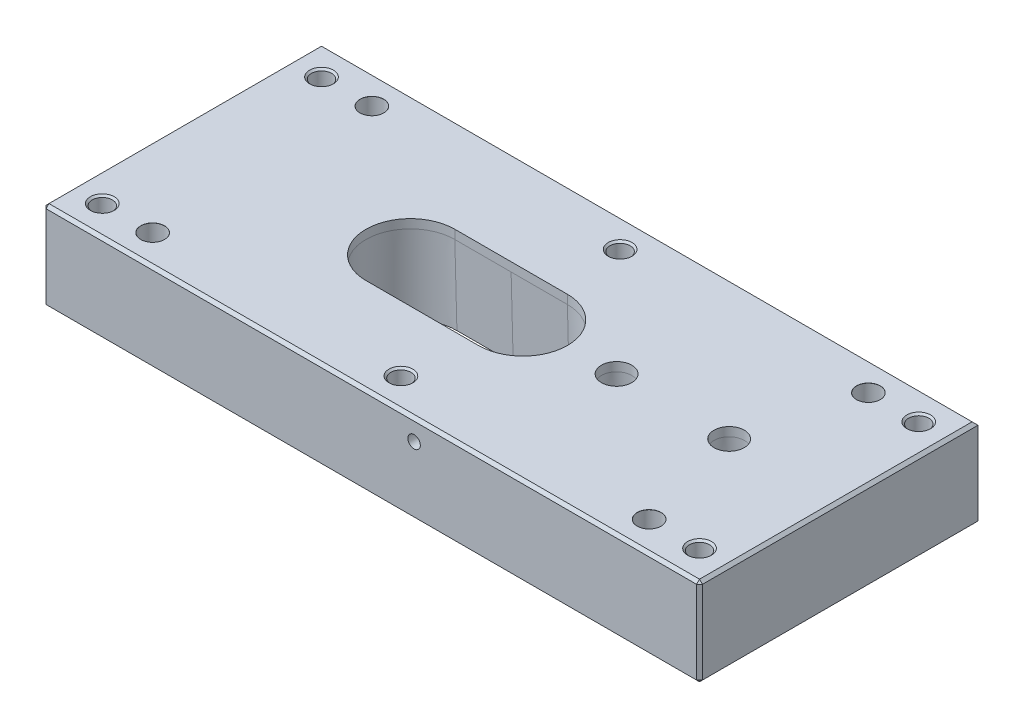
SolidWorks part; units mm, degrees
material "1.2316 (X36CrMo17)"
ref_plane "Front Plane" through (0, 0, 0) normal (0, 0, 1) x (1, 0, 0)
ref_plane "Top Plane" through (0, 0, 0) normal (0, 1, 0) x (1, 0, 0)
ref_plane "Right Plane" through (0, 0, 0) normal (1, 0, 0) x (0, 0, -1)
sketch "Sketch1" plane through (0, 0, 0) normal (0, 1, 0) x (1, 0, 0)
  line L1 (-110.8, 47) -> (110.8, 47)
  line L2 (-110.8, 47) -> (-110.8, -47)
  line L3 (-110.8, -47) -> (110.8, -47)
  line L4 (110.8, 47) -> (110.8, -47)
  line L5 (-110.8, 47) -> (110.8, -47) construction
  line L6 (-110.8, -47) -> (110.8, 47) construction
  point P0 (0, 0)
  dimension "D1" = 94
  dimension "D2" = 221.6
extrude "Boss-Extrude1" add sketch "Sketch1" against normal blind 30
sketch "Sketch2" plane through (0, 0, 0) normal (0, 1, 0) x (1, 0, 0)
  line L0 (-110.8, 0) -> (110.8, 0) construction
  line L1 (-110.8, 47) -> (-110.8, -47) construction
  line L2 (110.8, -47) -> (110.8, 47) construction
  line L3 (0, 47) -> (0, -47) construction
  line L4 (110.8, 47) -> (-110.8, 47) construction
  line L5 (-110.8, -47) -> (110.8, -47) construction
  line L6 (-33.8, 15) -> (4.2, 15)
  line L11 (-33.8, -15) -> (4.2, -15)
  line L12 (-48.8, 16.2329) -> (-48.8, -16.2329) construction
  arc A3 (-33.8, 15) -> (-33.8, -15) centre (-33.8, 0) ccw
  arc A4 (4.2, -15) -> (4.2, 15) centre (4.2, 0) ccw
  circle A5 centre (35.8, 0) radius 5.12
  circle A6 centre (73.8, 0) radius 5.12
  dimension "D1" = 15
  dimension "D3" = 10.24
  dimension "D2" = 38
  dimension "D4" = 38
  dimension "D5" = 62
  dimension "D6" = 69.6
extrude "Cut-Extrude1" cut sketch "Sketch2" against normal through all
ref_plane "Plane1" through (-14.8, 0, 0) normal (1, 0, 0) x (0, 0, -1)
sketch "Sketch3" plane through (-14.8, 0, 0) normal (1, 0, 0) x (0, 0, -1)
  line L0 (15, -3) -> (15.707, -30)
  line L1 (15, -30) -> (15, 0) construction
  line L2 (-47, -30) -> (47, -30) construction
  line L3 (15.707, -30) -> (15, -30)
  line L4 (15, -30) -> (15, -3)
  line L5 (51.7, 0) -> (-51.7, 0) construction
  dimension "D1" = 3
  dimension "D2" = 1.5
curve "CompCurve1"
sweep "Cut-Sweep1" cut profiles "Sketch3" path "CompCurve1"
ref_plane "Plane2" through (0, -3, 0) normal (0, 1, 0) x (1, 0, 0)
sketch "Sketch5" plane through (0, 0, 0) normal (0, 0, 1) x (1, 0, 0)
  line L0 (40.92, -3) -> (41.627, -30)
  line L1 (40.92, -30) -> (40.92, 0) construction
  line L2 (-110.8, -30) -> (110.8, -30) construction
  line L3 (41.627, -30) -> (40.92, -30)
  line L4 (40.92, -30) -> (40.92, -3)
  line L5 (51.7, 0) -> (-51.7, 0) construction
  dimension "D1" = 3
  dimension "D2" = 1.5
sweep "Cut-Sweep2" cut profiles "Sketch5" path edge at (35.8, 0, 5.12)
sketch "Sketch9" plane through (0, 0, 0) normal (0, 0, 1) x (1, 0, 0)
  line L0 (78.92, -3) -> (79.627, -30)
  line L1 (78.92, -30) -> (78.92, 0) construction
  line L2 (-110.8, -30) -> (110.8, -30) construction
  line L3 (79.627, -30) -> (78.92, -30)
  line L4 (78.92, -30) -> (78.92, -3)
  line L5 (51.7, 0) -> (-51.7, 0) construction
  dimension "D1" = 3
  dimension "D2" = 1.5
sweep "Cut-Sweep3" cut profiles "Sketch9" path edge at (73.8, 0, 5.12)
chamfer "Chamfer1" distance 1 angle 45 11 edges at (0, 0, 47) (-110.8, 0, 0) (0, 0, -47) (110.8, 0, 0) (-110.8, -15, 47) (-110.8, -15, -47) (-110.8, -30, 0) (0, -30, -47) (110.8, -30, 0) (0, -30, 47) (110.8, -15, 47)
sketch "Sketch10" plane through (0, 0, 47) normal (0, 0, 1) x (1, 0, 0)
  line L1 (-110.8, -29) -> (-110.8, -1) construction
  line L2 (-109.8, 0) -> (109.8, 0) construction
  point P0 (14.45, -7)
  dimension "D1" = 7
  dimension "D2" = 125.25
hole_wizard "M5 Tapped Hole1" positions "Sketch10" profile "Sketch11" tap size "M5" standard "ISO"
sketch "Sketch11" plane through (14.45, -7, 47) normal (1, 0, 0) x (0, -1, 0)
  line L0 (0, 0) -> (0, 15.2618)
  line L1 (0, 15.2618) -> (2.1, 14)
  line L2 (2.1, 14) -> (2.1, 0)
  line L5 (2.1, 0) -> (0, 0)
  line L10 (0, 15.2618) -> (-2.1, 14) construction
  line L11 (0, -6.35) -> (0, 107.95) construction
  dimension "Tap Drill Dia." = 4.2
  dimension "Tap Drill Depth" = 14
  dimension "Drill Angle" = 118
cosmetic thread "Hole Thread1" parameters "D1"=10, "D2"=5
hole_wizard "M8 Tapped Hole1" positions "Sketch14" profile "Sketch15" tap size "M8" standard "ISO" end condition through all
sketch "Sketch14" plane through (0, 0, 0) normal (0, 1, 0) x (1, 0, 0)
  line L0 (-110.8, -46) -> (-110.8, 46) construction
  line L1 (109.8, -47) -> (-109.8, -47) construction
  line L2 (-109.8, 47) -> (110.8, 47) construction
  line L3 (110.8, 47) -> (110.8, -46) construction
  line L4 (0, -13.2) -> (0, 13.2) construction
  point P0 (-100.8, -37)
  point P2 (-100.8, 37)
  point P4 (100.8, 37)
  point P6 (100.8, -37)
  point P21 (0, -37)
  point P25 (0, 37)
  dimension "D1" = 10
  dimension "D2" = 10
  dimension "D3" = 10
  dimension "D4" = 10
sketch "Sketch15" plane through (-100.8, 0, 37) normal (1, 0, 0) x (0, 0, 1)
  line L0 (0, 0) -> (0, 30)
  line L1 (0, 30) -> (4.025, 30)
  line L2 (3.4, 29.375) -> (3.4, 0.625)
  line L3 (3.4, 0.625) -> (4.025, 0)
  line L5 (4.025, 0) -> (0, 0)
  line L6 (-3.4, 0.625) -> (-4.025, 0) construction
  line L7 (4.025, 30) -> (3.4, 29.375)
  line L8 (-4.025, 30) -> (-3.4, 29.375) construction
  line L11 (0, -6.35) -> (0, 107.95) construction
  dimension "Thru Tap Drill Dia." = 6.8
  dimension "Thru Tap Drill Depth" = 30
  dimension "Near C'Sink Dia." = 8.05
  dimension "Near C'Sink Angle" = 90
  dimension "Far C'Sink Dia." = 8.05
  dimension "Far C'Sink Angle" = 90
cosmetic thread "Hole Thread2" parameters "D2"=8
cosmetic thread "Hole Thread3" parameters "D2"=8
cosmetic thread "Hole Thread4" parameters "D2"=8
cosmetic thread "Hole Thread5" parameters "D2"=8
cosmetic thread "Hole Thread6" parameters "D2"=8
cosmetic thread "Hole Thread7" parameters "D2"=8
hole_wizard "Ø8.0mm Dowel Hole1" positions "Sketch16" profile "Sketch17" hole size "Ø8.0" standard "ISO" end condition through all
sketch "Sketch16" plane through (0, 0, 0) normal (0, 1, 0) x (1, 0, 0)
  line L0 (-100.8, -37) -> (-83.8, -37) construction
  line L2 (100.8, 37) -> (83.8, 37) construction
  point P0 (-83.8, -37)
  point P2 (83.8, 37)
  dimension "D2" = 17
  dimension "D1" = 17
sketch "Sketch17" plane through (-83.8, 0, 37) normal (1, 0, 0) x (0, 0, 1)
  line L0 (0, 0) -> (0, 30)
  line L1 (0, 30) -> (4.025, 30)
  line L2 (4, 29.975) -> (4, 0.025)
  line L3 (4, 0.025) -> (4.025, 0)
  line L5 (4.025, 0) -> (0, 0)
  line L6 (-4, 0.025) -> (-4.025, 0) construction
  line L7 (4.025, 30) -> (4, 29.975)
  line L8 (-4.025, 30) -> (-4, 29.975) construction
  line L11 (0, -6.35) -> (0, 107.95) construction
  dimension "Thru Hole Dia." = 8
  dimension "Thru Hole Depth" = 30
  dimension "Near C'Sink Dia." = 8.05
  dimension "Near C'Sink Angle" = 90
  dimension "Far C'Sink Dia." = 8.05
  dimension "Far C'Sink Angle" = 90
mirror "Mirror1" about plane through (0, 0, 0) normal (0, 0, 1) of "Ø8.0mm Dowel Hole1"
